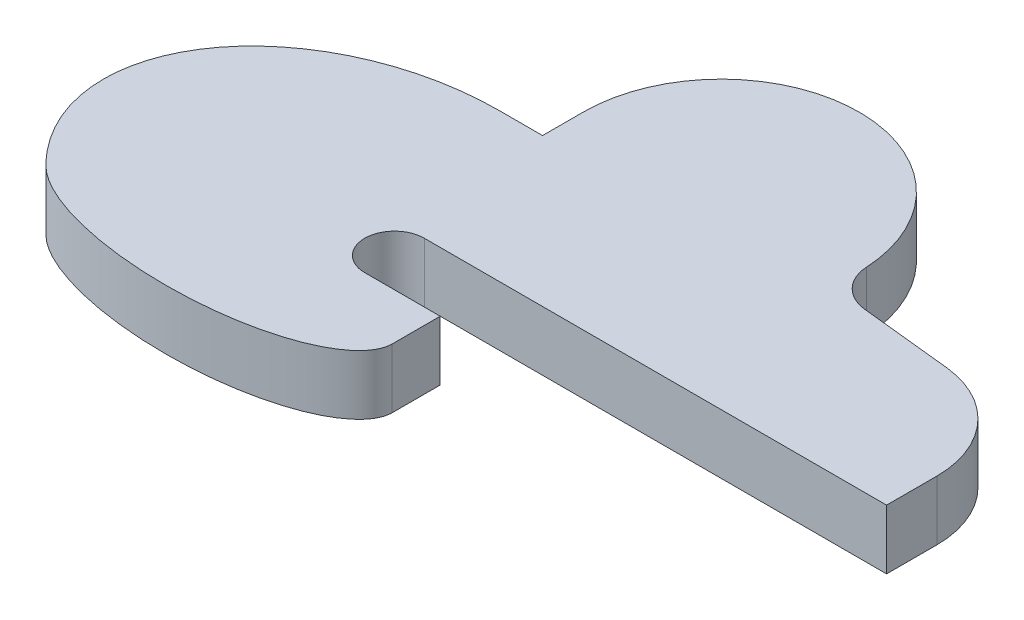
SolidWorks part; units mm, degrees
ref_plane "Front Plane" through (0, 0, 0) normal (0, 0, 1) x (1, 0, 0)
ref_plane "Top Plane" through (0, 0, 0) normal (0, 1, 0) x (1, 0, 0)
ref_plane "Right Plane" through (0, 0, 0) normal (1, 0, 0) x (0, 0, -1)
sketch "Sketch1" plane through (0, 0, 0) normal (0, 1, 0) x (1, 0, 0)
  line L0 (0, 0) -> (-3.8, 0)
  line L1 (-3.8, 3) -> (19.47, 3)
  line L2 (19.47, 3) -> (19.47, 5.5311)
  line L7 (-5.3, 10.4523) -> (-7.4659, 10.4523)
  line L9 (0, -2.4211) -> (0, 0)
  line L11 (10.378, 10.9888) -> (14.9926, 10.5037)
  line L12 (-5.3, 10.4523) -> (-5.3, 12.4959)
  arc A0 (-3.8, 0) -> (-3.8, 3) centre (-3.8, 1.5) cw
  arc A11 (-5.3, 12.4959) -> (8.5899, 12.8701) centre (1.65, 12.4959) cw
  arc A12 (8.5899, 12.8701) -> (10.378, 10.9888) centre (10.587, 12.9778) ccw
  arc A13 (19.47, 5.5311) -> (14.9926, 10.5037) centre (14.47, 5.5311) ccw
  ellipse E0 centre (-7.4659, 1.8573) end of major axis (-18.8159, 1.8573) minor radius 8.595 (-7.4659, 10.4523) -> (-16.4181, -3.4262) ccw
  ellipse E2 centre (-8.5084, -2.3155) end of major axis (0, -2.4211) minor radius 3.2414 (-16.4181, -3.4262) -> (0, -2.4211) ccw
  point P10 (1.4628, 19.4434)
  point P15 (8.476, 11.1887)
  point P17 (9.1373, 11.6)
  point P27 (-16.4181, -3.4262)
  point P44 (-5.3, 1.5)
  dimension "D1" = 17.19
  dimension "D4" = 1.5
  dimension "D5" = 11.35
  dimension "D6" = 6
  dimension "D7" = 2
  dimension "D10" = 25
  dimension "D11" = 1.0024
  dimension "D2" = 6.95
  dimension "D8" = 5
  dimension "13.48" = 23.27
  dimension "D9" = 3.8
  dimension "D37" = 8.6
  dimension "D12" = 3.2412
  dimension "D13" = 8.5084
  dimension "D14" = 4.6682
  dimension "D15" = 0.9316
  dimension "D17" = 7.2442
extrude "Boss-Extrude2" add sketch "Sketch1" along normal blind 3
